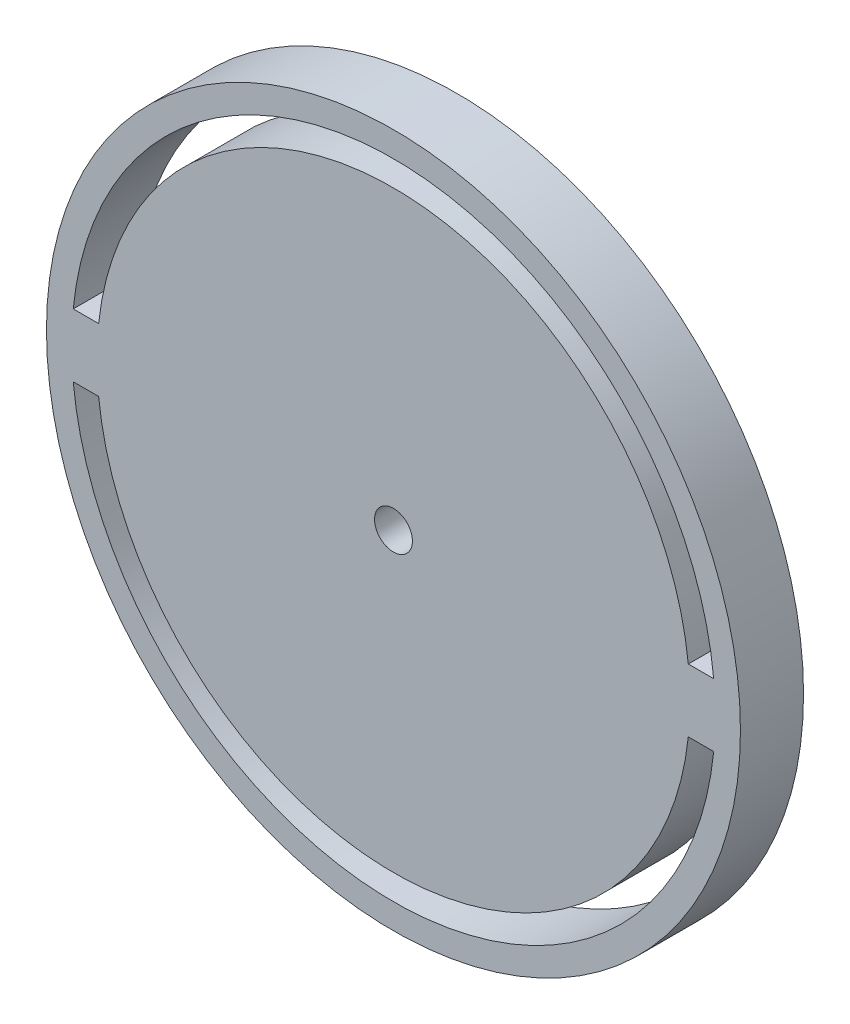
SolidWorks part; units mm, degrees
ref_plane "Front Plane" through (0, 0, 0) normal (0, 0, 1) x (1, 0, 0)
ref_plane "Top Plane" through (0, 0, 0) normal (0, 1, 0) x (1, 0, 0)
ref_plane "Right Plane" through (0, 0, 0) normal (1, 0, 0) x (0, 0, -1)
sketch "Sketch1" plane through (0, 0, 0) normal (0, 0, 1) x (1, 0, 0)
  circle A0 centre (0, 0) radius 55
  circle A1 centre (0, 0) radius 3
extrude "Boss-Extrude1" add sketch "Sketch1" along normal blind 10
sketch "Sketch2" plane through (0, 0, 10) normal (0, 0, 1) x (1, 0, 0)
  line L0 (-50.7543, -5) -> (-46.7333, -5)
  line L1 (-23.8394, 0) -> (23.8394, 0) construction
  line L2 (-50.7543, 5) -> (-46.7333, 5)
  line L4 (46.7333, -5) -> (50.7543, -5)
  line L5 (46.7333, 5) -> (50.7543, 5)
  arc A1 (-50.7543, -5) -> (50.7543, -5) centre (0, 0) ccw
  arc A2 (-46.7333, -5) -> (46.7333, -5) centre (0, 0) ccw
  arc A3 (46.7333, 5) -> (-46.7333, 5) centre (0, 0) ccw
  arc A4 (50.7543, 5) -> (-50.7543, 5) centre (0, 0) ccw
  point P7 (0, 0)
  dimension "D1" = 102
  dimension "D2" = 4
  dimension "D3" = 5
extrude "Cut-Extrude1" cut sketch "Sketch2" against normal blind 10
